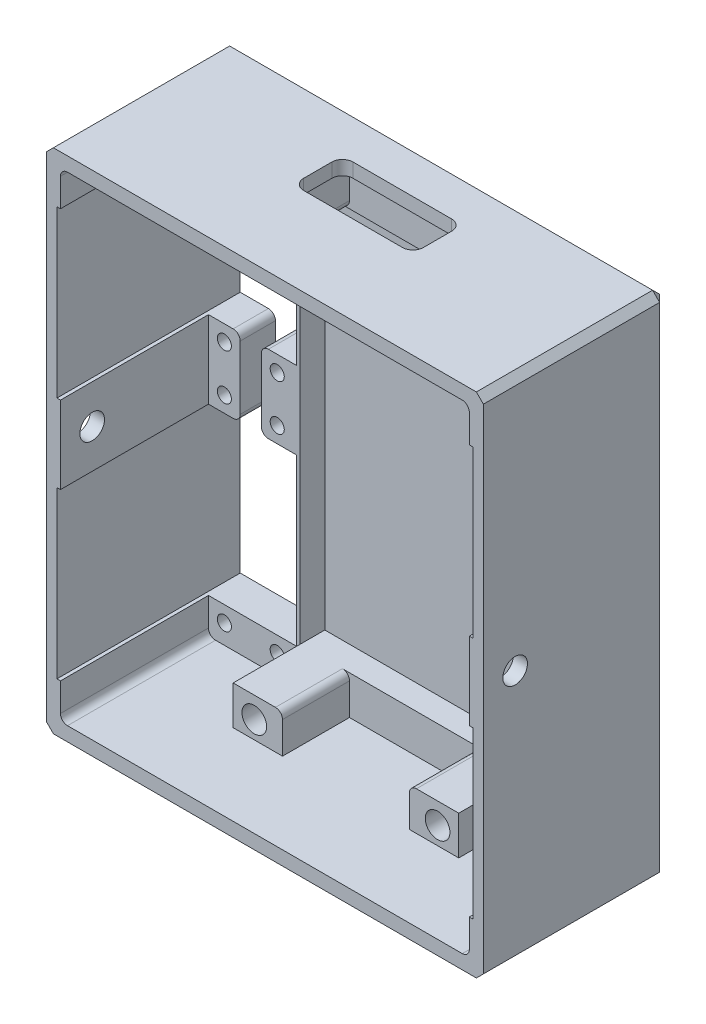
SolidWorks part; units mm, degrees
ref_plane "Front Plane" through (0, 0, 0) normal (0, 0, 1) x (1, 0, 0)
ref_plane "Top Plane" through (0, 0, 0) normal (0, 1, 0) x (1, 0, 0)
ref_plane "Right Plane" through (0, 0, 0) normal (1, 0, 0) x (0, 0, -1)
ref_plane "Plane1" through (0, -34, 0) normal (0, 1, 0) x (1, 0, 0)
sketch "Sketch1" plane through (0, -34, 0) normal (0, 1, 0) x (1, 0, 0)
  line L0 (-31, -22.5) -> (31, -22.5)
  line L1 (31, -22.5) -> (31, 3.5)
  line L2 (31, 3.5) -> (-31, 3.5)
  line L3 (-31, 3.5) -> (-31, -22.5)
extrude "Boss-Extrude1" add sketch "Sketch1" against normal blind 2
sketch "Sketch2" plane through (0, -34, 0) normal (0, 1, 0) x (-1, 0, 0)
  line L0 (-29, 22.5) -> (-29, 1.5)
  line L1 (-29, 1.5) -> (29, 1.5)
  line L2 (29, 1.5) -> (29, 22.5)
  line L3 (29, 22.5) -> (31, 22.5)
  line L4 (31, 22.5) -> (31, -3.5)
  line L5 (31, -3.5) -> (-31, -3.5)
  line L6 (-31, -3.5) -> (-31, 22.5)
  line L7 (-31, 22.5) -> (-29, 22.5)
extrude "Boss-Extrude2" add sketch "Sketch2" along normal blind 68
sketch "Sketch3" plane through (0, 34, 0) normal (0, 1, 0) x (-1, 0, 0)
  line L0 (31, -3.5) -> (-31, -3.5)
  line L1 (-31, -3.5) -> (-31, 22.5)
  line L2 (-31, 22.5) -> (31, 22.5)
  line L3 (31, 22.5) -> (31, -3.5)
extrude "Boss-Extrude3" add sketch "Sketch3" along normal blind 2
ref_plane "Plane2" through (29, 0, 0) normal (1, 0, 0) x (0, 0, -1)
sketch "Sketch4" plane through (29, 0, 0) normal (1, 0, 0) x (0, 0, -1)
  line L0 (-1.5, 29) -> (-1.5, -29)
  line L1 (-1.5, -29) -> (3.5, -29)
  line L2 (3.5, -29) -> (3.5, 29)
  line L3 (3.5, 29) -> (-1.5, 29)
extrude "Cut-Extrude1" cut sketch "Sketch4" against normal blind 12.5
sketch "Sketch5" plane through (29, 0, 0) normal (-1, 0, 0) x (0, 0, 1)
  line L0 (22.5, -29) -> (22.5, 29)
  line L1 (22.5, 29) -> (-3.5, 29)
  line L2 (-3.5, 29) -> (-3.5, -29)
  line L3 (-3.5, -29) -> (22.5, -29)
extrude "Cut-Extrude2" cut sketch "Sketch5" against normal blind 0.5
ref_plane "Plane3" through (-29, 0, 0) normal (-1, 0, 0) x (0, -1, 0)
sketch "Sketch6" plane through (-29, 0, 0) normal (-1, 0, 0) x (0, -1, 0)
  line L0 (29, 1.5) -> (-29, 1.5)
  line L1 (-29, 1.5) -> (-29, -3.5)
  line L2 (-29, -3.5) -> (29, -3.5)
  line L3 (29, -3.5) -> (29, 1.5)
extrude "Cut-Extrude3" cut sketch "Sketch6" against normal blind 12.5
sketch "Sketch7" plane through (-29, 0, 0) normal (1, 0, 0) x (0, 0, -1)
  line L0 (-22.5, 29) -> (-22.5, -29)
  line L1 (-22.5, -29) -> (3.5, -29)
  line L2 (3.5, -29) -> (3.5, 29)
  line L3 (3.5, 29) -> (-22.5, 29)
extrude "Cut-Extrude4" cut sketch "Sketch7" against normal blind 0.5
sketch "Sketch8" plane through (-16.5, 0, 0) normal (-1, 0, 0) x (0, 0, 1)
  line L0 (1.5, 5.5) -> (1.5, -5.5)
  line L1 (1.5, -5.5) -> (-3.5, -5.5)
  line L2 (-3.5, -5.5) -> (-3.5, 5.5)
  line L3 (-3.5, 5.5) -> (1.5, 5.5)
extrude "Boss-Extrude4" add sketch "Sketch8" along normal blind 5
sketch "Sketch9" plane through (29.5, 0, 0) normal (-1, 0, 0) x (0, 0, 1)
  line L0 (22.5, -5.5) -> (-3.5, -5.5)
  line L1 (-3.5, -5.5) -> (-3.5, 5.5)
  line L2 (-3.5, 5.5) -> (22.5, 5.5)
  line L3 (22.5, 5.5) -> (22.5, -5.5)
extrude "Boss-Extrude5" add sketch "Sketch9" along normal blind 5
sketch "Sketch10" plane through (16.5, 0, 0) normal (1, 0, 0) x (0, 0, -1)
  line L0 (3.5, 5.5) -> (3.5, -5.5)
  line L1 (3.5, -5.5) -> (-1.5, -5.5)
  line L2 (-1.5, -5.5) -> (-1.5, 5.5)
  line L3 (-1.5, 5.5) -> (3.5, 5.5)
extrude "Boss-Extrude6" add sketch "Sketch10" along normal blind 5
sketch "Sketch11" plane through (-29.5, 0, 0) normal (1, 0, 0) x (0, 0, -1)
  line L0 (3.5, 5.5) -> (3.5, -5.5)
  line L1 (3.5, -5.5) -> (-22.5, -5.5)
  line L2 (-22.5, -5.5) -> (-22.5, 5.5)
  line L3 (-22.5, 5.5) -> (3.5, 5.5)
extrude "Boss-Extrude7" add sketch "Sketch11" along normal blind 5
sketch "Sketch12" plane through (0, 34, 0) normal (0, -1, 0) x (1, 0, 0)
  line L0 (-9, 11) -> (-9, 1.5)
  line L1 (-9, 1.5) -> (-16, 1.5)
  line L2 (-16, 1.5) -> (-16, 11)
  line L3 (-16, 11) -> (-9, 11)
extrude "Boss-Extrude8" add sketch "Sketch12" along normal blind 5.5
sketch "Sketch13" plane through (0, -34, 0) normal (0, 1, 0) x (-1, 0, 0)
  line L0 (-9, 11) -> (-9, 1.5)
  line L1 (-9, 1.5) -> (-16, 1.5)
  line L2 (-16, 1.5) -> (-16, 11)
  line L3 (-16, 11) -> (-9, 11)
extrude "Boss-Extrude9" add sketch "Sketch13" along normal blind 5.5
sketch "Sketch14" plane through (0, 0, 1.5) normal (0, 0, 1) x (1, 0, 0)
  line L0 (16, -28.5) -> (16, 28.5)
  line L1 (16, 28.5) -> (-16, 28.5)
  line L2 (-16, 28.5) -> (-16, -28.5)
  line L3 (-16, -28.5) -> (16, -28.5)
extrude "Cut-Extrude5" cut sketch "Sketch14" against normal blind 3.5
sketch "Sketch15" plane through (0, -34, 0) normal (0, 1, 0) x (-1, 0, 0)
  line L0 (9, 1.5) -> (9, 11)
  line L1 (9, 11) -> (16, 11)
  line L2 (16, 11) -> (16, 1.5)
  line L3 (16, 1.5) -> (9, 1.5)
extrude "Boss-Extrude10" add sketch "Sketch15" along normal blind 5.5
sketch "Sketch16" plane through (0, 34, 0) normal (0, -1, 0) x (1, 0, 0)
  line L0 (9, 11) -> (16, 11)
  line L1 (16, 11) -> (16, 1.5)
  line L2 (16, 1.5) -> (9, 1.5)
  line L3 (9, 1.5) -> (9, 11)
extrude "Boss-Extrude11" add sketch "Sketch16" along normal blind 5.5
sketch "Sketch17" plane through (0, 5.5, 0) normal (0, 1, 0) x (-1, 0, 0)
  line L0 (-24.5, 22.5) -> (-29, 22.5)
  line L1 (-29, 22.5) -> (-29, 1.5)
  line L2 (-29, 1.5) -> (-24.5, 1.5)
  line L3 (-24.5, 1.5) -> (-24.5, 22.5)
extrude "Cut-Extrude6" cut sketch "Sketch17" against normal up to next
sketch "Sketch18" plane through (0, -5.5, 0) normal (0, -1, 0) x (1, 0, 0)
  line L0 (-29, 22.5) -> (-29, 1.5)
  line L1 (-29, 1.5) -> (-24.5, 1.5)
  line L2 (-24.5, 1.5) -> (-24.5, 22.5)
  line L3 (-24.5, 22.5) -> (-29, 22.5)
extrude "Cut-Extrude7" cut sketch "Sketch18" against normal up to next
sketch "Sketch19" plane through (0, 36, 0) normal (0, 1, 0) x (-1, 0, 0)
  line L0 (-8.5, 3) -> (8.5, 3)
  line L1 (8.5, 3) -> (8.5, 10)
  line L2 (8.5, 10) -> (-8.5, 10)
  line L3 (-8.5, 10) -> (-8.5, 3)
extrude "Cut-Extrude8" cut sketch "Sketch19" against normal up to next
hole_wizard "Ø2.0 (2) Diameter Hole1" positions "Sketch21" profile "Sketch20" hole size "Ø2.0" standard "ANSI Metric"
sketch "Sketch21" plane through (0, 0, -3.5) normal (0, 0, -1) x (-1, 0, 0)
  point P0 (-19.25, 3.25)
  point P1 (-19.25, -3.25)
  point P2 (19.25, 3.25)
  point P3 (19.25, -3.25)
  point P4 (-19.25, 31.25)
  point P5 (-26.75, 31.25)
  point P6 (-26.75, 3.25)
  point P7 (-26.75, -3.25)
  point P8 (19.25, -31.25)
  point P9 (-26.75, -31.25)
  point P10 (-19.25, -31.25)
  point P11 (26.75, -31.25)
  point P12 (26.75, -3.25)
  point P13 (26.75, 3.25)
  point P14 (26.75, 31.25)
  point P15 (19.25, 31.25)
sketch "Sketch20" plane through (19.25, 3.25, -3.5) normal (1, 0, 0) x (0, 1, 0)
  line L0 (0, 0) -> (0, 26)
  line L1 (0, 26) -> (1, 26)
  line L2 (1, 26) -> (1, 0)
  line L5 (1, 0) -> (0, 0)
  line L11 (0, -6.35) -> (0, 107.95) construction
  dimension "Thru Hole Dia." = 2
  dimension "Thru Hole Depth" = 26
hole_wizard "Ø3.5 (3.5) Diameter Hole1" positions "Sketch23" profile "Sketch22" hole size "Ø3.5" standard "ANSI Metric"
sketch "Sketch23" plane through (0, 0, -3.5) normal (0, 0, -1) x (-1, 0, 0)
  point P0 (-13, 31.5)
  point P1 (13, 31.5)
  point P2 (-13, -31.5)
  point P3 (13, -31.5)
sketch "Sketch22" plane through (13, 31.5, -3.5) normal (1, 0, 0) x (0, 1, 0)
  line L0 (0, 0) -> (0, 26)
  line L1 (0, 26) -> (1.75, 26)
  line L2 (1.75, 26) -> (1.75, 0)
  line L5 (1.75, 0) -> (0, 0)
  line L11 (0, -6.35) -> (0, 107.95) construction
  dimension "Thru Hole Dia." = 3.5
  dimension "Thru Hole Depth" = 26
hole_wizard "Ø3.5 (3.5) Diameter Hole2" positions "Sketch25" profile "Sketch24" hole size "Ø3.5" standard "ANSI Metric"
sketch "Sketch25" plane through (-29, 0, 0) normal (1, 0, 0) x (0, 0, -1)
  point P0 (-18, 0)
sketch "Sketch24" plane through (-29, 0, 18) normal (0, 1, 0) x (0, 0, -1)
  line L0 (0, 0) -> (0, 2)
  line L1 (0, 2) -> (1.75, 2)
  line L2 (1.75, 2) -> (1.75, 0)
  line L5 (1.75, 0) -> (0, 0)
  line L11 (0, -6.35) -> (0, 107.95) construction
  dimension "Thru Hole Dia." = 3.5
  dimension "Thru Hole Depth" = 2
hole_wizard "Ø3.5 (3.5) Diameter Hole3" positions "Sketch27" profile "Sketch26" hole size "Ø3.5" standard "ANSI Metric"
sketch "Sketch27" plane through (31, 0, 0) normal (1, 0, 0) x (0, 0, -1)
  point P0 (-18, 0)
sketch "Sketch26" plane through (31, 0, 18) normal (0, 1, 0) x (0, 0, -1)
  line L0 (0, 0) -> (0, 62)
  line L1 (0, 62) -> (1.75, 62)
  line L2 (1.75, 62) -> (1.75, 0)
  line L5 (1.75, 0) -> (0, 0)
  line L11 (0, -6.35) -> (0, 107.95) construction
  dimension "Thru Hole Dia." = 3.5
  dimension "Thru Hole Depth" = 62
chamfer "Chamfer1" distance 1.5833 angle 46.975 4 edges at (11.25, 31.5, -3.5) (-14.75, 31.5, -3.5) (11.25, -31.5, -3.5) (-14.75, -31.5, -3.5)
chamfer "Chamfer2" distance 1 angle 45 8 edges at (31, -36, 9.5) (31, 0, -3.5) (31, 36, 9.5) (-31, -36, 9.5) (0, -36, -3.5) (0, 36, -3.5) (-31, 0, -3.5) (-31, 36, 9.5)
fillet "Fillet1" radius 1 16 edges at (-21.5, 5.5, -1) (-21.5, -5.5, -1) (24.5, -5.5, -1) (21.5, 5.5, -1) (21.5, -5.5, -1) (-24.5, 5.5, -1) (-29, -34, 12) (-9, 28.5, 6.25) (29, -34, 12) (9, -28.5, 6.25) (-29, 34, 12) (29, 34, 12) (-9, -28.5, 6.25) (9, 28.5, 6.25) (24.5, 5.5, -1) (-24.5, -5.5, -1)
fillet "Fillet2" radius 1.5 4 edges at (8.5, 35, 3) (-8.5, 35, 3) (-8.5, 35, 10) (8.5, 35, 10)
sketch "Sketch28" plane through (0, 0, -3.5) normal (0, 0, -1) x (-1, 0, 0)
  line L0 (-30, -35) -> (30, -35)
  line L1 (30, -35) -> (30, 35)
  line L2 (30, 35) -> (-30, 35)
  line L3 (-30, 35) -> (-30, -35)
  circle A0 centre (-26.75, -31.25) radius 1
  circle A1 centre (-19.2628, -31.25) radius 1.0128
  circle A2 centre (19.25, -31.25) radius 1
  circle A3 centre (26.75, -31.25) radius 1
  circle A4 centre (-26.75, -3.25) radius 1
  circle A5 centre (-26.75, 3.25) radius 1
  circle A6 centre (-19.25, -3.25) radius 1
  circle A7 centre (-19.25, 3.25) radius 1
  circle A8 centre (-26.75, 31.25) radius 1
  circle A9 centre (-19.25, 31.25) radius 1
  circle A10 centre (19.25, -3.25) radius 1
  circle A11 centre (26.75, -3.25) radius 1
  circle A12 centre (19.25, 3.25) radius 1
  circle A13 centre (26.75, 3.25) radius 1
  circle A14 centre (19.25, 31.25) radius 1
  circle A15 centre (26.75, 31.25) radius 1
  circle A16 centre (-13, -31.5) radius 3.3333
  circle A17 centre (-13, -31.5) radius 1.7536
  circle A18 centre (-13, 31.5) radius 1.75
  circle A19 centre (-13, 31.5) radius 3.3333
  circle A20 centre (13, 31.5) radius 1.75
  circle A21 centre (13, 31.5) radius 3.3333
  circle A22 centre (13, -31.5) radius 1.75
  circle A23 centre (13, -31.5) radius 3.3333
